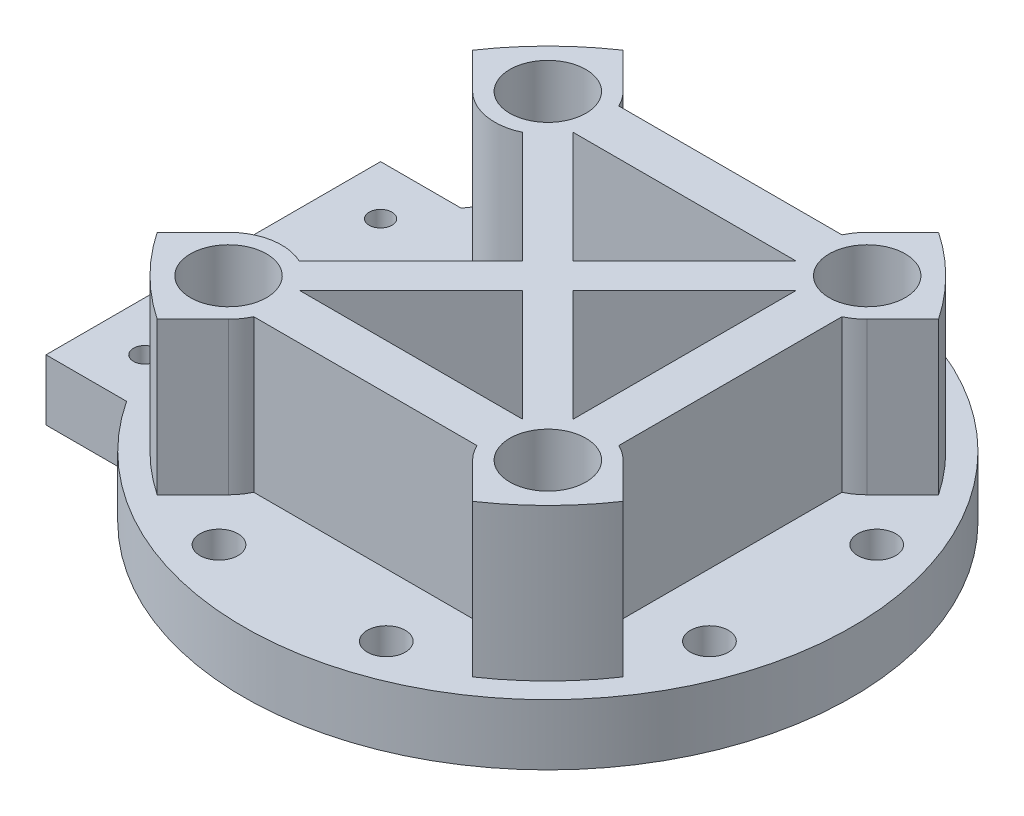
SolidWorks part; units mm, degrees
ref_plane "Front Plane" through (0, 0, 0) normal (0, 0, 1) x (1, 0, 0)
ref_plane "Top Plane" through (0, 0, 0) normal (0, 1, 0) x (1, 0, 0)
ref_plane "Right Plane" through (0, 0, 0) normal (1, 0, 0) x (0, 0, -1)
sketch "Sketch1" plane through (0, 0, 0) normal (0, 1, 0) x (1, 0, 0)
  line L3 (-44, -22) -> (-44, 22)
  line L5 (-44, 22) -> (-33.4066, 22)
  line L6 (-44, -22) -> (-33.4066, -22)
  circle A0 centre (0, 0) radius 40
  circle A10 centre (32.25, 11) radius 2.5
  circle A12 centre (32.25, -11) radius 2.5
  circle A13 centre (-11, -32.25) radius 2.5
  circle A14 centre (11, -32.25) radius 2.5
  circle A15 centre (-11, 32.25) radius 2.5
  circle A16 centre (11, 32.25) radius 2.5
  circle A19 centre (-22, 0) radius 9.5
extrude "Boss-Extrude2" add sketch "Sketch1" along normal blind 8 contours A0 L5 L3 L6 | A0 A19 A16 A15 A14 A13 A12 A10
sketch "Sketch3" plane through (0, 8, 0) normal (0, 1, 0) x (1, 0, 0)
  circle A0 centre (-37.5, 15.5) radius 1.5
  circle A1 centre (-6.5, 15.5) radius 1.5
  circle A2 centre (-6.5, -15.5) radius 1.5
  circle A3 centre (-37.5, -15.5) radius 1.5
extrude "Cut-Extrude1" cut sketch "Sketch3" against normal blind 8
sketch "Sketch4" plane through (0, 8, 0) normal (0, 1, 0) x (1, 0, 0)
  line L0 (24, 14) -> (24, -14.4463)
  line L5 (18, 14) -> (18, -14.1115)
  line L6 (18, 14) -> (18, 14.6754)
  line L7 (24, 14) -> (24, 14.6754)
  line L8 (13.75, 18) -> (-14.2433, 18)
  line L9 (-14.2433, 18) -> (14.6754, 18)
  line L10 (-13, 24) -> (14.6754, 24)
  line L11 (14.6754, 24) -> (-13.8906, 24)
  line L12 (-14.6754, 18) -> (18, -14.6754)
  line L13 (14.6754, -18) -> (-18, 14.6754)
  line L14 (-14.6754, -18) -> (18, 14.6754)
  line L15 (-14.2433, 18) -> (-14.6754, 18)
  line L16 (14.6754, 24) -> (-14.6754, 24)
  line L17 (18, 14.6754) -> (18, -14.6754)
  line L18 (24, 14.6754) -> (24, -14.6754)
  line L19 (14, -24) -> (-14.6754, -24)
  line L20 (-14.6754, -24) -> (14.6754, -24)
  line L21 (14, -18) -> (-14.6754, -18)
  line L22 (14, -18) -> (14.6754, -18)
  line L23 (14.6754, 18) -> (-18, -14.6754)
  line L24 (-22, 0) -> (-44, 0)
  line L25 (-44, -22) -> (-44, 22) construction
  line L26 (-16.0503, -25.9497) -> (-20.7407, -30.6402)
  line L28 (-25.9497, -16.0503) -> (-30.6402, -20.7407)
  line L31 (25.9497, -16.0503) -> (30.6402, -20.7407)
  line L33 (16.0503, -25.9497) -> (20.7407, -30.6402)
  line L34 (15.1741, -24.9549) -> (15.3314, -25.1453)
  line L37 (25.9497, 16.0503) -> (30.6402, 20.7407)
  line L39 (16.0503, 25.9497) -> (20.7407, 30.6402)
  line L43 (-25.9497, 16.0503) -> (-30.6402, 20.7407)
  line L44 (-16.0503, 25.9497) -> (-20.7407, 30.6402)
  circle A8 centre (21, -21) radius 5
  circle A11 centre (32.25, 11) radius 3.5
  circle A12 centre (32.25, -11) radius 3.5
  circle A13 centre (11, -32.25) radius 3.5
  circle A14 centre (-11, -32.25) radius 3.5
  circle A15 centre (0, 0) radius 37
  circle A16 centre (21, 21) radius 5
  circle A17 centre (21, 21) radius 7
  circle A18 centre (21, -21) radius 7
  circle A19 centre (-21, -21) radius 5
  circle A20 centre (-21, -21) radius 7
  circle A21 centre (-21, 21) radius 5
  circle A22 centre (-21, 21) radius 7
  dimension "D1" = 22
extrude "Boss-Extrude6" add sketch "Sketch4" along normal blind 20 contours A20 A19 | A20 L28 A15 L26 | A20 L14 L13 L23 | A20 L19 L20 A18 L22 L21 | A18 A8 | A18 L33 A15 L31 | A18 L12 L14 L13 | A18 L18 L0 L7 A17 L6 L5 L17 | A17 L23 L12 L14 | L12 L23 L13 L14 | A22 L13 L23 L12 | A22 L15 L8 L9 A17 L10 L11 L16 | A17 A16 | A17 L37 A15 L39 | A22 L44 A15 L43 | A22 A21
